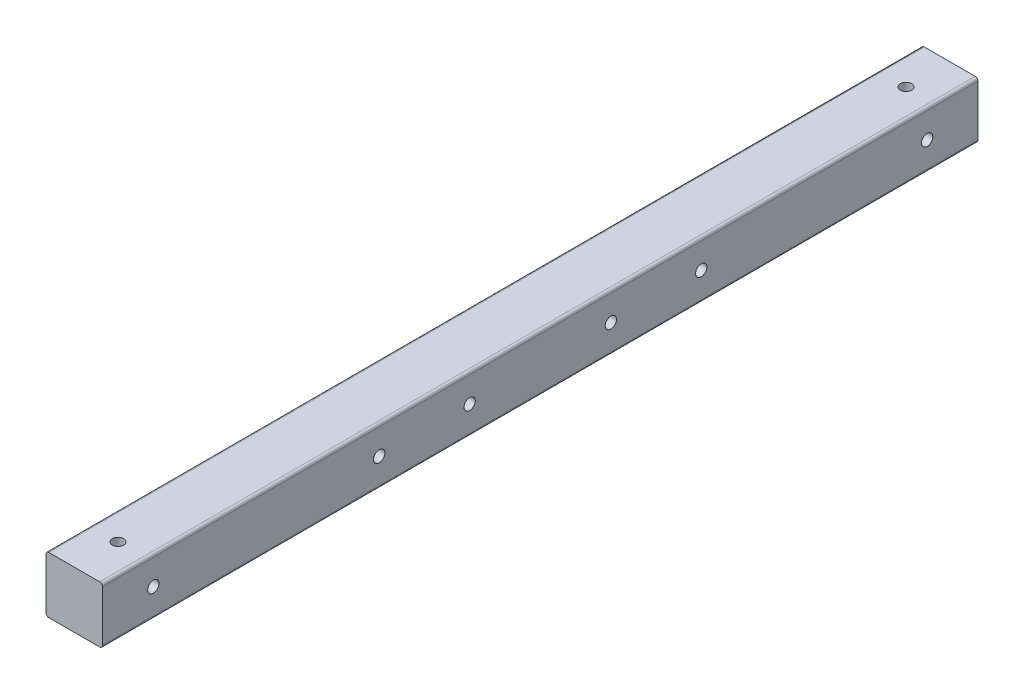
SolidWorks part; units mm, degrees
ref_plane "前视基准面" through (0, 0, 0) normal (0, 0, 1) x (1, 0, 0)
ref_plane "上视基准面" through (0, 0, 0) normal (0, 1, 0) x (1, 0, 0)
ref_plane "右视基准面" through (0, 0, 0) normal (1, 0, 0) x (0, 0, -1)
sketch "草图1" plane through (0, 0, 0) normal (0, 0, 1) x (1, 0, 0)
  line L1 (0, 0) -> (20, 0)
  line L2 (0, 0) -> (0, 20)
  line L3 (0, 20) -> (20, 20)
  line L4 (20, 0) -> (20, 20)
  dimension "D1" = 20
  dimension "D2" = 20
extrude "凸台-拉伸1" add sketch "草图1" along normal blind 310
fillet "圆角1" radius 1 4 edges at (0, 0, 155) (20, 0, 155) (20, 20, 155) (0, 20, 155)
sketch "草图2" plane through (0, 0, 0) normal (-1, 0, 0) x (0, 0, 1)
  line L0 (0, 19) -> (0, 1) construction
  line L1 (310, 0) -> (0, 0) construction
  line L2 (310, 19) -> (310, 1) construction
  circle A0 centre (98, 10) radius 2
  circle A1 centre (212, 10) radius 2
  circle A2 centre (130, 10) radius 2
  circle A3 centre (180, 10) radius 2
  circle A4 centre (18, 10) radius 2
  circle A5 centre (292, 10) radius 2
  dimension "D3" = 4
  dimension "D1" = 98
  dimension "D2" = 10
  dimension "D4" = 98
  dimension "D5" = 32
  dimension "D6" = 32
  dimension "D7" = 18
  dimension "D8" = 18
extrude "切除-拉伸1" cut sketch "草图2" against normal blind 310
sketch "草图3" plane through (0, 0, 0) normal (0, -1, 0) x (1, 0, 0)
  line L0 (1, 0) -> (19, 0) construction
  line L1 (0, 0) -> (0, 310) construction
  line L2 (1, 310) -> (19, 310) construction
  circle A0 centre (10, 15.5) radius 2
  circle A1 centre (10, 294.5) radius 2
  point P8 (0, 0)
  dimension "D3" = 4
  dimension "D4" = 15.5
  dimension "D1" = 15.5
  dimension "D2" = 10
extrude "切除-拉伸2" cut sketch "草图3" against normal blind 20
